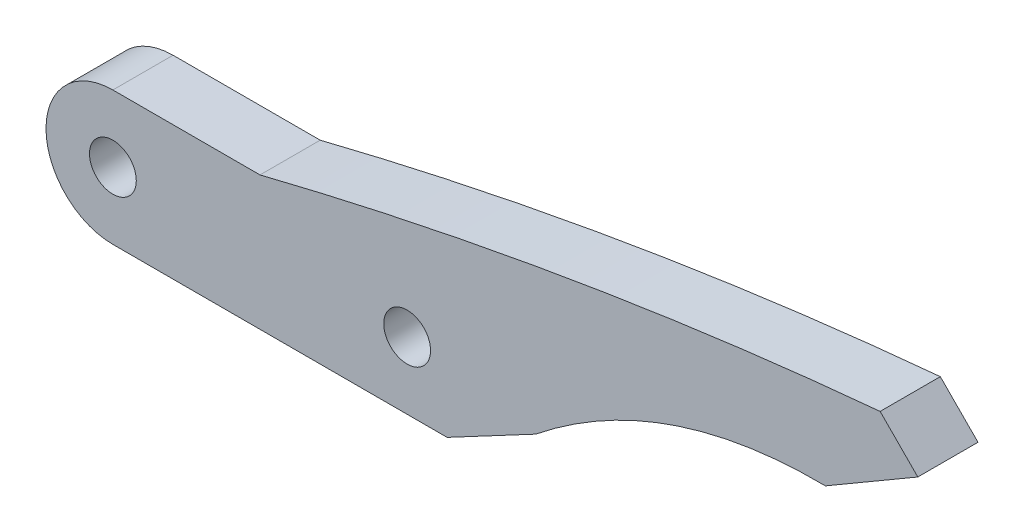
SolidWorks part; units mm, degrees
ref_plane "Front Plane" through (0, 0, 0) normal (0, 0, 1) x (1, 0, 0)
ref_plane "Top Plane" through (0, 0, 0) normal (0, 1, 0) x (1, 0, 0)
ref_plane "Right Plane" through (0, 0, 0) normal (1, 0, 0) x (0, 0, -1)
sketch "Sketch1" plane through (0, 0, 0) normal (0, 0, 1) x (1, 0, 0)
  line L0 (11, 0) -> (-11, 0) construction
  line L1 (0, 0) -> (0, 3.152) construction
  line L3 (-16, 5) -> (16, 5)
  line L4 (-16, 5) -> (-16, -5)
  line L5 (-16, -5) -> (16, -5)
  line L6 (16, 5) -> (16, -5)
  line L7 (-16, 5) -> (16, -5) construction
  line L8 (-16, -5) -> (16, 5) construction
  circle A0 centre (-11, 0) radius 1.75
  circle A1 centre (-11, 0) radius 5
  circle A2 centre (11, 0) radius 5
  circle A3 centre (11, 0) radius 1.75
  point P4 (0, 0)
  dimension "D2" = 3.5
  dimension "D3" = 10
  dimension "D1" = 22
extrude "Boss-Extrude1" add sketch "Sketch1" along normal blind 4.5 contours A1 A0 | A2 A3 | L5 A2 L3 A1
sketch "Sketch2" plane through (0, 0, 4.5) normal (0, 0, 1) x (1, 0, 0)
  line L0 (46.364, 12.87) -> (49.1808, 10.03)
  line L1 (49.1808, 10.03) -> (42.27, 6)
  line L2 (-11, -5) -> (11, -5) construction
  line L3 (11, 0) -> (11, -5) construction
  line L4 (20.61, -1.48) -> (13.99, -5)
  line L5 (13.99, -5) -> (11, -5)
  line L6 (-11, 5) -> (11, 5) construction
  line L7 (0, 5) -> (11, 5)
  arc A0 (11, -5) -> (11, 5) centre (11, 0) ccw construction
  arc A1 (11, -5) -> (11, 5) centre (11, 0) ccw
  spline S0 degree 2 poles (42.27, 6) (30.1462, 6.1573) (20.61, -1.48) knots 0 0 0 1 1 1
  spline S1 degree 2 poles (0, 5) (22.8855, 10.7079) (46.364, 12.87) knots 0 0 0 1 1 1
  dimension "D1" = 4
  dimension "D2" = 8
  dimension "D3" = 17.87
  dimension "D4" = 15.03
  dimension "D5" = 2.99
  dimension "D6" = 9.45
  dimension "D7" = 3.52
  dimension "D8" = 9.61
  dimension "D9" = 20.52
  dimension "D10" = 31.27
  dimension "D11" = 28.001
  dimension "D12" = 13.52
  dimension "D13" = 15.07
extrude "Boss-Extrude2" add sketch "Sketch2" against normal up to surface (4.5 mm away) up to face at (-9.25, 0, 0)
